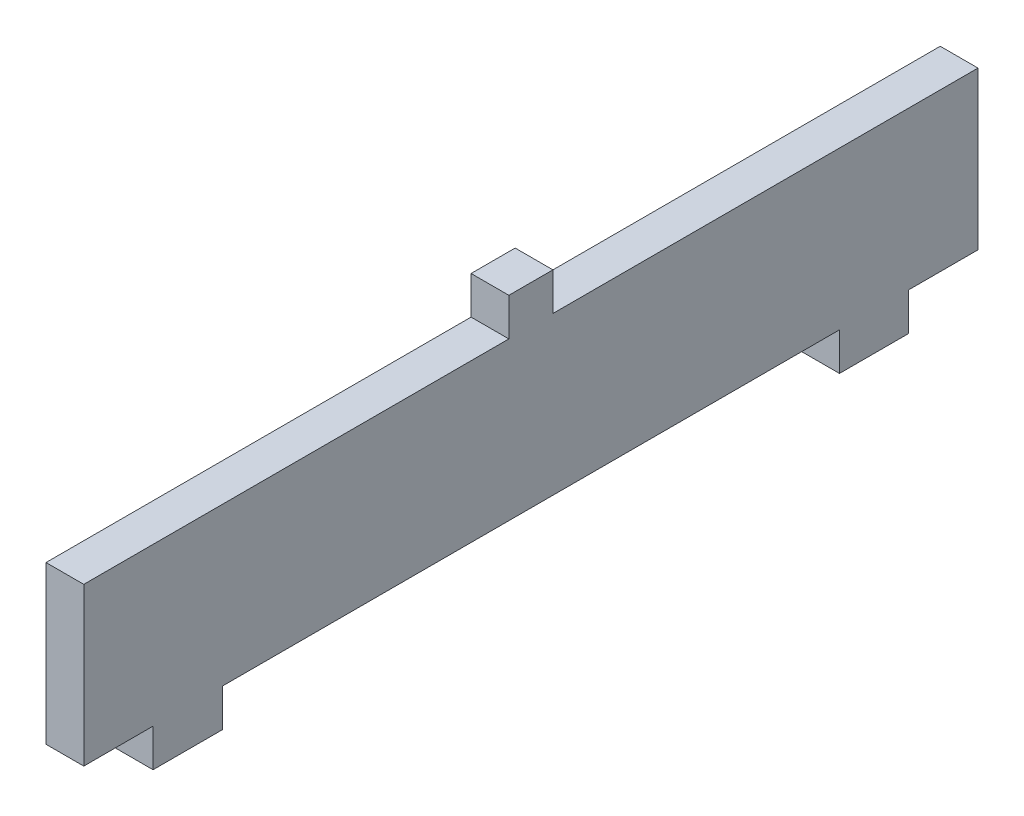
SolidWorks part; units mm, degrees
ref_plane "Alzado" through (0, 0, 0) normal (0, 0, 1) x (1, 0, 0)
ref_plane "Planta" through (0, 0, 0) normal (0, 1, 0) x (1, 0, 0)
ref_plane "Vista lateral" through (0, 0, 0) normal (1, 0, 0) x (0, 0, -1)
sketch "Croquis1" plane through (0, 0, 0) normal (1, 0, 0) x (0, 0, -1)
  line L0 (1.75, 6.25) -> (35.5, 6.25)
  line L1 (-35.5, -6.25) -> (-30, -6.25)
  line L2 (-35.5, -6.25) -> (-35.5, 6.25)
  line L3 (-35.5, 6.25) -> (-1.75, 6.25)
  line L4 (35.5, -6.25) -> (35.5, 6.25)
  line L5 (-35.5, -6.25) -> (35.5, 6.25) construction
  line L6 (-35.5, 6.25) -> (35.5, -6.25) construction
  line L7 (-24.5, -6.25) -> (24.5, -6.25)
  line L8 (-1.75, 6.25) -> (-1.75, 9.25)
  line L9 (-1.75, 9.25) -> (1.75, 9.25)
  line L10 (1.75, 6.25) -> (1.75, 9.25)
  line L12 (24.5, -6.25) -> (24.5, -9.25)
  line L13 (24.5, -9.25) -> (30, -9.25)
  line L14 (30, -6.25) -> (30, -9.25)
  line L15 (30, -6.25) -> (35.5, -6.25)
  line L16 (-30, -6.25) -> (-30, -9.25)
  line L17 (-30, -9.25) -> (-24.5, -9.25)
  line L18 (-24.5, -6.25) -> (-24.5, -9.25)
  point P0 (0, 0)
  point P18 (0, 9.25)
  point P19 (-24.5, -7.75)
  dimension "D1" = 71
  dimension "D2" = 12.5
  dimension "D3" = 3
  dimension "D4" = 3
  dimension "D5" = 3.5
  dimension "D6" = 5.5
  dimension "D7" = 5.5
  dimension "D8" = 49
  dimension "D9" = 5.5
extrude "Saliente-Extruir1" add sketch "Croquis1" along normal blind 3
